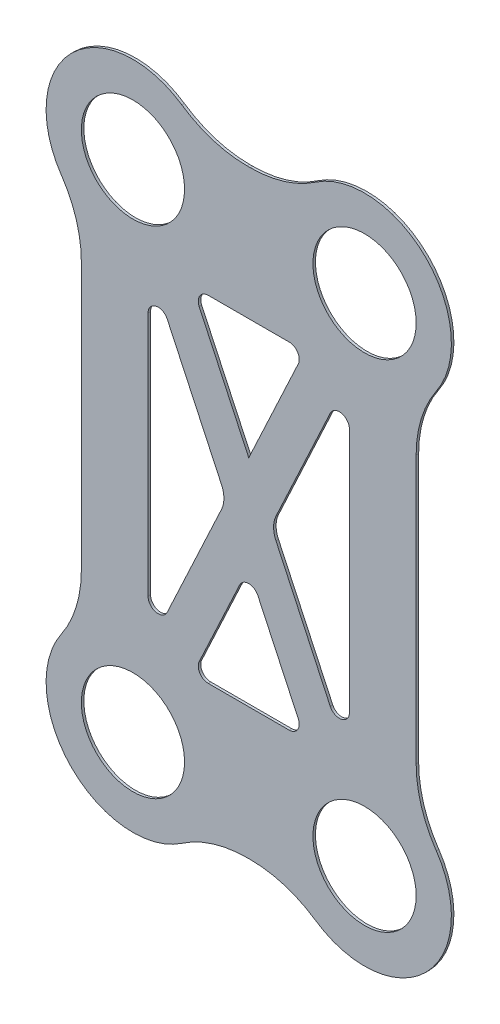
SolidWorks part; units mm, degrees
ref_plane "前视基准面" through (0, 0, 0) normal (0, 0, 1) x (1, 0, 0)
ref_plane "上视基准面" through (0, 0, 0) normal (0, 1, 0) x (1, 0, 0)
ref_plane "右视基准面" through (0, 0, 0) normal (1, 0, 0) x (0, 0, -1)
other "Configuration Table"
sketch "草图1" plane through (0, 0, 0) normal (0, 0, 1) x (1, 0, 0)
  line L0 (-33.25, 0) -> (33.25, 0) construction
  line L1 (-33.25, 59.5) -> (33.25, 59.5)
  line L2 (-33.25, 59.5) -> (-33.25, -59.5)
  line L3 (-33.25, -59.5) -> (33.25, -59.5)
  line L4 (33.25, 59.5) -> (33.25, -59.5)
  line L5 (-33.25, 59.5) -> (33.25, -59.5) construction
  line L6 (-33.25, -59.5) -> (33.25, 59.5) construction
  line L7 (0, 59.5) -> (0, -59.5) construction
  line L8 (-40.25, 66.5) -> (-40.25, -66.5)
  line L9 (-40.25, -66.5) -> (40.25, -66.5)
  line L10 (40.25, 66.5) -> (40.25, -66.5)
  line L11 (-40.25, 66.5) -> (40.25, 66.5)
  line L12 (-12.75, -49.25) -> (12.75, -49.25) construction
  circle A0 centre (-23, 49.25) radius 10.25
  circle A1 centre (23, 49.25) radius 10.25
  circle A2 centre (-23, -49.25) radius 10.25
  circle A3 centre (23, -49.25) radius 10.25
  arc A4 (-9.1256, 59.5) -> (-33.25, 35.3756) centre (-23, 49.25) ccw
  arc A5 (-33.25, -35.3756) -> (-9.1256, -59.5) centre (-23, -49.25) ccw
  arc A6 (33.25, 35.3756) -> (9.1256, 59.5) centre (23, 49.25) ccw
  arc A7 (9.1256, -59.5) -> (33.25, -35.3756) centre (23, -49.25) ccw
  circle A8 centre (-23, 49.25) radius 17.25 construction
  circle A9 centre (23, 49.25) radius 17.25 construction
  circle A10 centre (-23, -49.25) radius 17.25 construction
  circle A11 centre (23, -49.25) radius 17.25 construction
  point P0 (0, 0)
  dimension "D3" = 20.5
  dimension "D4" = 7
  dimension "D1" = 46
  dimension "D2" = 119
extrude "凸台-拉伸2" add sketch "草图1" along normal blind 0.5 contours L1 A4 L2 | A6 L1 L4 | A3 L4 A1 L1 A0 L2 A2 L3 | A0 L1 L2 | A1 L4 L1 | L2 A5 L3 | A2 L2 L3 | A7 L4 L3 | A3 L3 L4
fillet "圆角1" radius 23 8 edges at (9.1256, -59.5, 0.25) (-9.1256, -59.5, 0.25) (-9.1256, 59.5, 0.25) (9.1256, 59.5, 0.25) (33.25, 35.3756, 0.25) (-33.25, 35.3756, 0.25) (-33.25, -35.3756, 0.25) (33.25, -35.3756, 0.25)
sketch "草图2" plane through (0, 0, 0) normal (0, 0, -1) x (-1, 0, 0)
  line L0 (-2.2073, -4.7266) -> (2.2073, 4.7266) construction
  line L1 (-23, 49.25) -> (2.2073, -4.7266) construction
  line L2 (-20, 33.3729) -> (11.1706, -33.3729)
  line L3 (-11.1706, -33.3729) -> (20, 33.3729)
  line L4 (-11.1706, 33.3729) -> (20, -33.3729)
  line L5 (-20, -33.3729) -> (11.1706, 33.3729)
  line L6 (-33.25, 0) -> (33.25, 0) construction
  line L7 (-33.25, 26.5674) -> (-33.25, -26.5674) construction
  line L8 (33.25, 26.5674) -> (33.25, -26.5674) construction
  line L9 (0, 59.5125) -> (0, -59.5125) construction
  line L10 (-20, 33.3729) -> (-20, -33.3729)
  line L11 (-11.1706, 33.3729) -> (11.1706, 33.3729)
  line L12 (-11.1706, -33.3729) -> (11.1706, -33.3729)
  line L13 (20, 33.3729) -> (20, -33.3729)
  line L14 (-19.3757, 50.9425) -> (26.8032, -47.9405) construction
  line L15 (-26.6243, 47.5575) -> (19.5546, -51.3256) construction
  line L16 (-19.5739, -51.3669) -> (26.7707, 47.8711) construction
  line L17 (-23.1982, -49.6744) -> (23.1465, 49.5637) construction
  line L18 (-26.8225, -47.9818) -> (19.5222, 51.2562) construction
  line L19 (-23, 49.25) -> (23.1789, -49.6331) construction
  dimension "D4" = 20
  dimension "D2" = 4
  dimension "D3" = 4
extrude "切除-拉伸1" cut sketch "草图2" against normal blind 55 contours L13 L3 L4 | L11 L4 L5 | L2 L10 L5 | L3 L12 L2
fillet "圆角2" radius 2 9 edges at (11.1706, 33.3729, 0.25) (-11.1706, 33.3729, 0.25) (11.1706, -33.3729, 0.25) (-11.1706, -33.3729, 0.25) (0, -9.4532, 0.25) (-20, -33.3729, 0.25) (-20, 33.3729, 0.25) (20, -33.3729, 0.25) (20, 33.3729, 0.25)
fillet "圆角3" radius 5 2 edges at (4.4147, 0, 0.25) (-4.4147, 0, 0.25)
